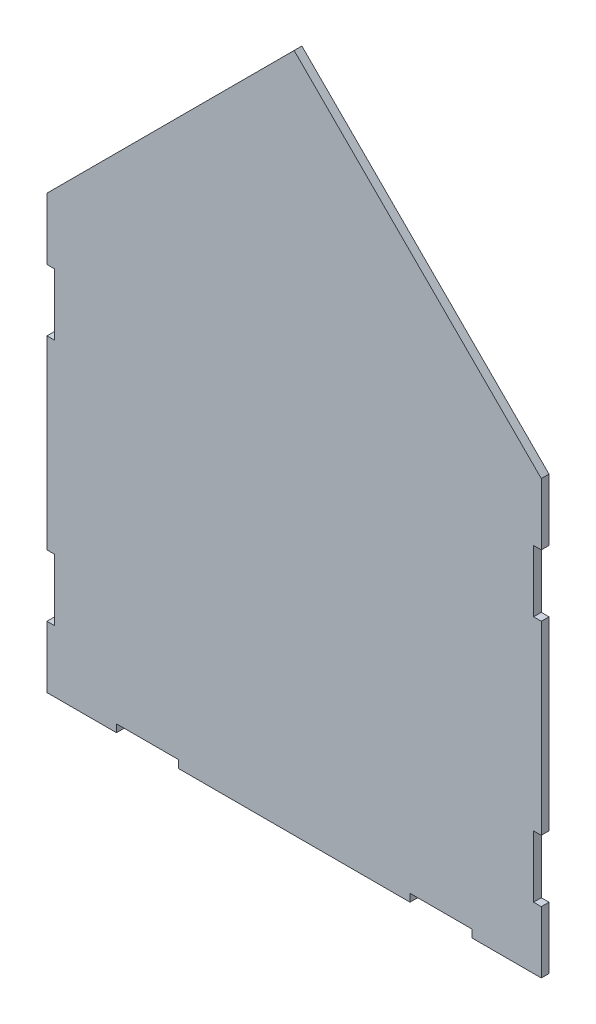
SolidWorks part; units mm, degrees
ref_plane "Front Plane" through (0, 0, 0) normal (0, 0, 1) x (1, 0, 0)
ref_plane "Top Plane" through (0, 0, 0) normal (0, 1, 0) x (1, 0, 0)
ref_plane "Right Plane" through (0, 0, 0) normal (1, 0, 0) x (0, 0, -1)
sketch "Sketch2" plane through (0, 0, 0) normal (0, 0, 1) x (1, 0, 0)
  line L0 (0.8968, 279.4) -> (-100.7032, 177.8)
  line L1 (-100.7032, 177.8) -> (102.4968, 177.8) construction
  line L2 (102.4968, 177.8) -> (0.8968, 279.4)
  line L3 (-100.7032, 177.8) -> (-100.7032, 152.4)
  line L4 (-100.7032, 152.4) -> (-97.5282, 152.4)
  line L5 (-97.5282, 152.4) -> (-97.5282, 127)
  line L6 (-97.5282, 127) -> (-100.7032, 127)
  line L7 (-100.7032, 127) -> (-100.7032, 50.8)
  line L8 (-100.7032, 50.8) -> (-97.5282, 50.8)
  line L9 (-97.5282, 50.8) -> (-97.5282, 25.4)
  line L10 (-97.5282, 25.4) -> (-100.7032, 25.4)
  line L11 (-100.7032, 25.4) -> (-100.7032, 0)
  line L12 (-100.7032, 0) -> (-72.1282, 0)
  line L13 (102.4968, 0) -> (102.4968, 25.4)
  line L14 (102.4968, 25.4) -> (99.3218, 25.4)
  line L15 (99.3218, 25.4) -> (99.3218, 50.8)
  line L16 (99.3218, 50.8) -> (102.4968, 50.8)
  line L17 (102.4968, 50.8) -> (102.4968, 127)
  line L18 (102.4968, 127) -> (99.3218, 127)
  line L19 (99.3218, 127) -> (99.3218, 152.4)
  line L20 (99.3218, 152.4) -> (102.4968, 152.4)
  line L21 (102.4968, 152.4) -> (102.4968, 177.8)
  line L22 (-72.1282, 0) -> (-72.1282, 3.175)
  line L23 (-72.1282, 3.175) -> (-46.7282, 3.175)
  line L24 (-46.7282, 3.175) -> (-46.7282, 0)
  line L25 (-46.7282, 0) -> (48.5218, 0)
  line L26 (48.5218, 0) -> (48.5218, 3.175)
  line L27 (48.5218, 3.175) -> (73.9218, 3.175)
  line L28 (73.9218, 3.175) -> (73.9218, 0)
  line L29 (73.9218, 0) -> (102.4968, 0)
  dimension "D1" = 203.2
  dimension "D2" = 101.6
  dimension "D3" = 25.4
  dimension "D4" = 95.25
  dimension "D5" = 25.4
  dimension "D6" = 25.4
  dimension "D7" = 3.175
  dimension "D8" = 25.4
  dimension "D15" = 76.2
extrude "Boss-Extrude1" add sketch "Sketch2" along normal blind 3.175
